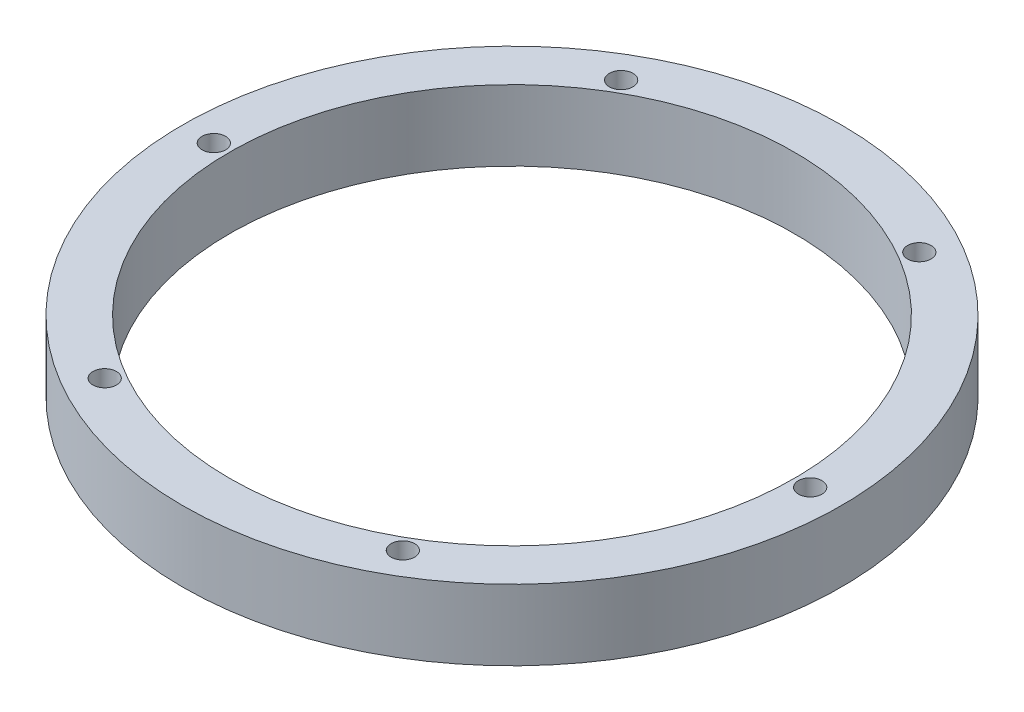
SolidWorks part; units mm, degrees
material "Acrylic (Medium-high impact)"
ref_plane "Front Plane" through (0, 0, 0) normal (0, 0, 1) x (1, 0, 0)
ref_plane "Top Plane" through (0, 0, 0) normal (0, 1, 0) x (1, 0, 0)
ref_plane "Right Plane" through (0, 0, 0) normal (1, 0, 0) x (0, 0, -1)
sketch "Sketch1" plane through (0, 0, 0) normal (0, 1, 0) x (1, 0, 0)
  line L0 (0, 0) -> (88.676, 0) construction
  line L1 (88.676, 0) -> (-95.0922, 0) construction
  line L2 (0, 0) -> (37.1099, -64.2763) construction
  line L3 (37.1099, -64.2763) -> (-35.0592, 60.7243) construction
  line L4 (-44.2878, -76.7087) -> (0, 0) construction
  line L5 (0, 0) -> (36.8411, 63.8106) construction
  circle A0 centre (0, 0) radius 36
  circle A1 centre (0, 0) radius 42
  circle A2 centre (0, 0) radius 38 construction
  circle A3 centre (19, -32.909) radius 1.5
  circle A4 centre (-19, -32.909) radius 1.5
  circle A5 centre (-38, 0) radius 1.5
  circle A6 centre (-19, 32.909) radius 1.5
  circle A7 centre (19, 32.909) radius 1.5
  circle A8 centre (38, 0) radius 1.5
  dimension "D1" = 60
  dimension "D2" = 60
extrude "Boss-Extrude1" add sketch "Sketch1" along normal blind 9
